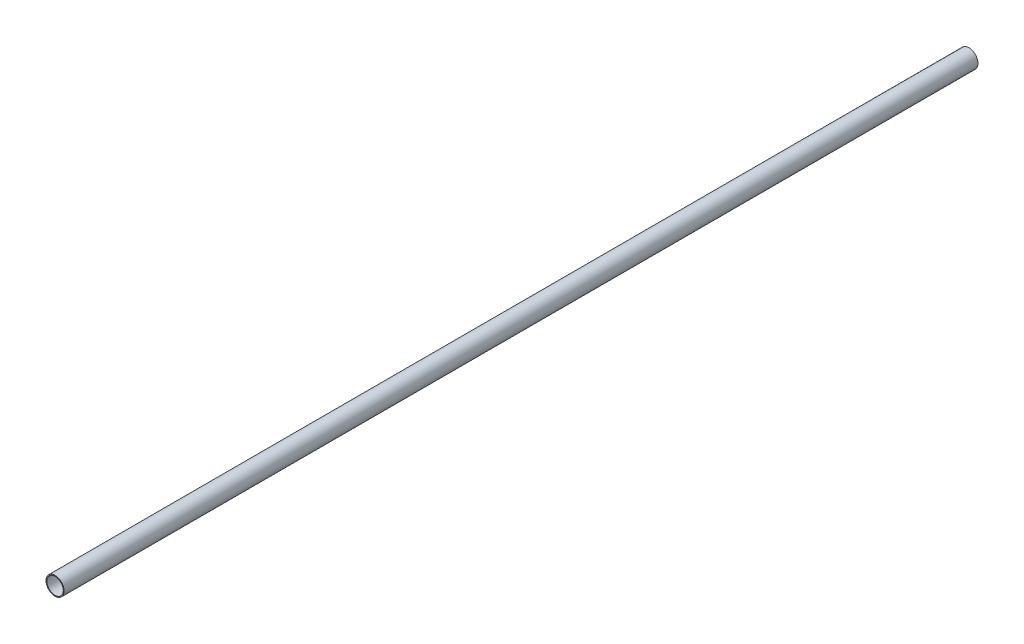
SolidWorks part; units mm, degrees
material "Brass"
ref_plane "Front Plane" through (0, 0, 0) normal (0, 0, 1) x (1, 0, 0)
ref_plane "Top Plane" through (0, 0, 0) normal (0, 1, 0) x (1, 0, 0)
ref_plane "Right Plane" through (0, 0, 0) normal (1, 0, 0) x (0, 0, -1)
sketch "Sketch1" plane through (0, 0, 0) normal (0, 0, 1) x (1, 0, 0)
  circle A0 centre (0, 0) radius 1.8
  circle A1 centre (0, 0) radius 1.9844
  dimension "D1" = 3.9688
  dimension "D2" = 3.6
extrude "Boss-Extrude1" add sketch "Sketch1" along normal blind 200
